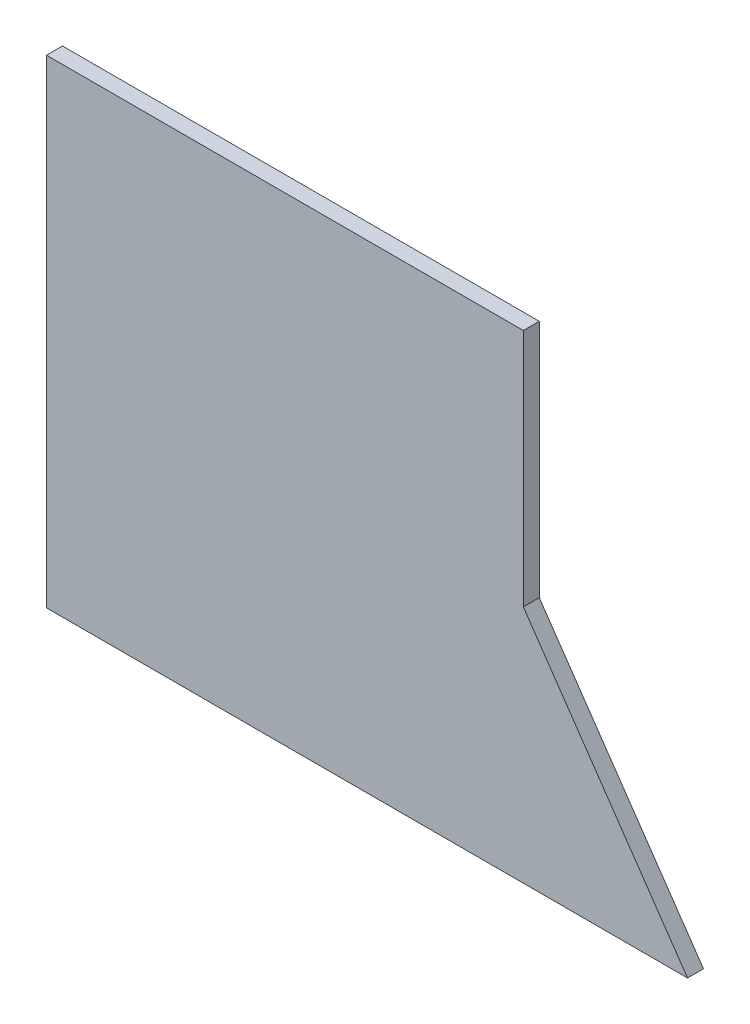
SolidWorks part; units mm, degrees
ref_plane "Front Plane" through (0, 0, 0) normal (0, 0, 1) x (1, 0, 0)
ref_plane "Top Plane" through (0, 0, 0) normal (0, 1, 0) x (1, 0, 0)
ref_plane "Right Plane" through (0, 0, 0) normal (1, 0, 0) x (0, 0, -1)
sketch "Sketch2" plane through (0, 0, 0) normal (0, 0, 1) x (1, 0, 0)
  line L0 (0, 0.35) -> (0.2977, 0.35)
  line L1 (0.2977, 0.35) -> (0.2977, 0.05)
  line L2 (0.2977, -0.25) -> (-0.3, -0.25)
  line L3 (0.2977, 0.05) -> (0.5035, -0.25)
  line L4 (-0.3, -0.25) -> (-0.3, 0.35)
  line L5 (-0.3, 0.35) -> (0, 0.35)
  line L6 (0.5035, -0.25) -> (0.2977, -0.25)
  dimension "D1" = 0.35
  dimension "D2" = 0.35
  dimension "D3" = 0.6
sketch "Sketch1" plane through (0, 0, 0) normal (1, 0, 0) x (0, 0, -1)
  line L0 (-0.025, 0.35) -> (0.025, 0.35)
  arc A0 (0.025, 0.35) -> (-0.025, 0.35) centre (0, 0.35) ccw
  dimension "D1" = 0.05
extrude "Boss-Extrude1" add sketch "Sketch2" along normal mid plane 0.02
